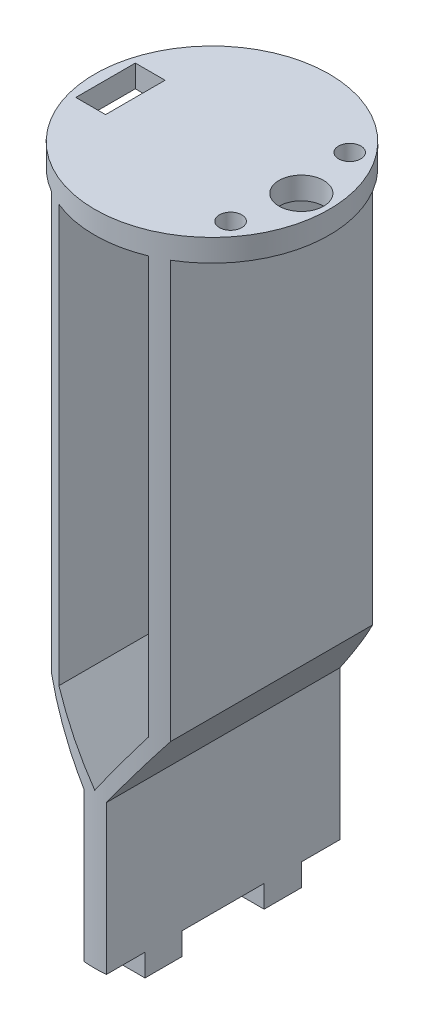
SolidWorks part; units mm, degrees
ref_plane "Plan de face" through (0, 0, 0) normal (0, 0, 1) x (1, 0, 0)
ref_plane "Plan de dessus" through (0, 0, 0) normal (0, 1, 0) x (1, 0, 0)
ref_plane "Plan de droite" through (0, 0, 0) normal (1, 0, 0) x (0, 0, -1)
sketch "Esquisse1" plane through (0, 0, 0) normal (0, 0, 1) x (1, 0, 0)
  line L0 (3, 0) -> (9.5, 9.2857)
  line L1 (0, 0) -> (3, 0)
  line L2 (0, 0) -> (0, -20)
  line L3 (0, -20) -> (3, -20)
  line L4 (3, 0) -> (3, -20)
  line L5 (9.5, 9.2857) -> (9.5, 68.2857)
  line L6 (9.5, 68.2857) -> (-6.5, 68.2857)
  line L7 (-6.5, 68.2857) -> (-6.5, 9.2857)
  line L8 (-6.5, 9.2857) -> (0, 0)
  line L9 (7.5, 9.2857) -> (7.5, 65.2857)
  line L10 (7.5, 65.2857) -> (-4.5, 65.2857)
  line L11 (-4.5, 65.2857) -> (-4.5, 9.2857)
  line L13 (1.5, 10) -> (1.5, -5.2331) construction
  line L14 (1.5, 0) -> (1.5, 9.2713) construction
  line L15 (-4.5, 9.2857) -> (1.5, 0.7143)
  line L16 (1.5, 0.7143) -> (7.5, 9.2857)
  dimension "D1" = 2
  dimension "D2" = 3
  dimension "D3" = 2
  dimension "D4" = 20
  dimension "D5" = 12
  dimension "D6" = 56
  dimension "D7" = 3
  dimension "D8" = 145.008
extrude "Boss.-Extru.1" add sketch "Esquisse1" along normal blind 33
sketch "Esquisse3" plane through (0, 68.2857, 0) normal (0, 1, 0) x (1, 0, 0)
  line L0 (-6.5, -16.5) -> (9.5, -16.5) construction
  line L1 (-6.5, -33) -> (-6.5, 0) construction
  line L2 (9.5, -33) -> (9.5, 0) construction
  circle A0 centre (1.5, -16.5) radius 16.5
  dimension "D1" = 33
extrude "Boss.-Extru.2" add sketch "Esquisse3" against normal blind 3
sketch "Esquisse4" plane through (0, 65.2857, 0) normal (0, -1, 0) x (1, 0, 0)
  line L0 (-6.5, 16.5) -> (-12.8, 16.5) construction
  line L1 (-6.5, 2.0691) -> (-6.5, 30.9309) construction
  line L2 (-12.8, 16.5) -> (-12.8, 20.5)
  line L3 (-12.8, 20.5) -> (-8.8, 20.5)
  line L4 (-8.8, 20.5) -> (-8.8, 12.5)
  line L5 (-8.8, 12.5) -> (-12.8, 12.5)
  line L6 (-12.8, 12.5) -> (-12.8, 16.5)
  line L7 (9.5, 16.5) -> (13.5, 16.5) construction
  line L8 (9.5, 30.9309) -> (9.5, 2.0691) construction
  line L9 (12, 8.5) -> (9.5, 8.5) construction
  circle A0 centre (13.5, 16.5) radius 3
  circle A1 centre (12, 8.5) radius 1.5
  circle A2 centre (12, 24.5) radius 1.5
  dimension "D5" = 4
  dimension "D6" = 2.5
  dimension "D7" = 3
  dimension "D8" = 6
  dimension "D1" = 6.3
  dimension "D2" = 4
  dimension "D3" = 8
  dimension "D4" = 8
  dimension "D9" = 8
extrude "Enlèv. mat.-Extru.1" cut sketch "Esquisse4" against normal through all
sketch "Esquisse5" plane through (0, -20, 0) normal (0, -1, 0) x (1, 0, 0)
  line L0 (3, 33) -> (3, 0) construction
  line L1 (3, 22) -> (0, 22)
  line L2 (3, 22) -> (3, 27)
  line L3 (3, 27) -> (0, 27)
  line L4 (0, 22) -> (0, 27)
  line L5 (0, 33) -> (0, 0) construction
  line L6 (0, 33) -> (0, 0) construction
  line L7 (0, 11) -> (3, 11)
  line L8 (0, 11) -> (0, 6)
  line L9 (0, 6) -> (3, 6)
  line L10 (3, 11) -> (3, 6)
  point P12 (0, 16.5)
  dimension "D1" = 5
  dimension "D2" = 5
  dimension "D3" = 11
  dimension "D4" = 5.5
extrude "Boss.-Extru.3" add sketch "Esquisse5" along normal blind 3
sketch "Esquisse2" plane through (0, 68.2857, 0) normal (0, 1, 0) x (1, 0, 0)
  line L0 (-6.5, -31.9654) -> (-5.9387, -31.9654) construction
  line L1 (-6.5, -33) -> (-6.5, -30.9309) construction
  line L2 (1.5, 0) -> (1.5, -33) construction
  line L4 (9.5, 0) -> (-6.5, 0) construction
  line L6 (9.5, -33) -> (-6.5, -33) construction
  circle A0 centre (1.5, -16.5) radius 15.75
  dimension "D1" = 31.5
extrude "Enlèv. de mat.-Extru.-Mince2" cut sketch "Esquisse2" against normal blind 90 and the other way blind 30 thin
